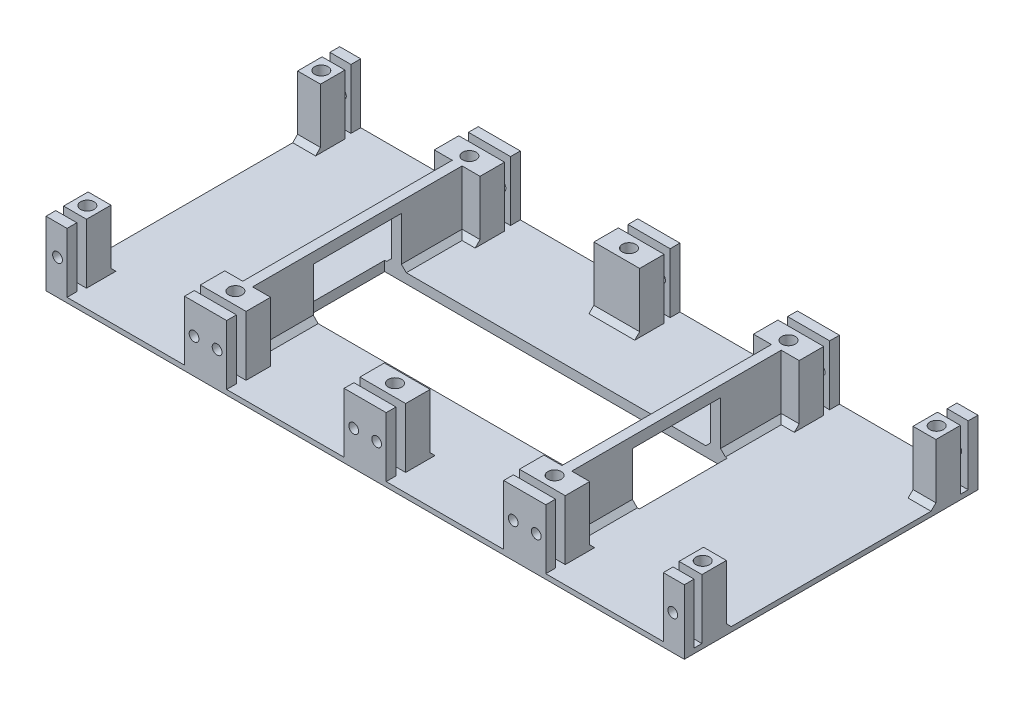
SolidWorks part; units mm, degrees
ref_plane "Alzado" through (0, 0, 0) normal (0, 0, 1) x (1, 0, 0)
ref_plane "Planta" through (0, 0, 0) normal (0, 1, 0) x (1, 0, 0)
ref_plane "Vista lateral" through (0, 0, 0) normal (1, 0, 0) x (0, 0, -1)
sketch "Croquis1" plane through (0, 0, 0) normal (0, 1, 0) x (1, 0, 0)
  line L1 (-65.2, 30) -> (65.2, 30)
  line L2 (-65.2, 30) -> (-65.2, -30)
  line L3 (-65.2, -30) -> (65.2, -30)
  line L4 (65.2, 30) -> (65.2, -30)
  line L5 (-65.2, 30) -> (65.2, -30) construction
  line L6 (-65.2, -30) -> (65.2, 30) construction
  point P0 (0, 0)
  dimension "D1" = 60
  dimension "D2" = 130.4
extrude "Saliente-Extruir1" add sketch "Croquis1" along normal blind 2
sketch "Croquis3" plane through (0, 0, 30) normal (0, 0, 1) x (1, 0, 0)
  line L0 (0, 0) -> (0, 26.1175) construction
  line L1 (-66, 8.1) -> (49934, 8.1) construction
  line L2 (-65.2, 2) -> (0, 2)
  line L3 (-65.2, 2) -> (-65.2, 14.2)
  line L4 (-65.2, 14.2) -> (0, 14.2)
  line L5 (0, 2) -> (0, 14.2)
  line L6 (-32.6, 14.2) -> (-32.6, 50014.2) construction
  line L7 (-65.2, 2) -> (65.2, 2) construction
  circle A0 centre (-62.85, 8.1) radius 1
  circle A1 centre (-34.95, 8.1) radius 1
  circle A4 centre (-30.25, 8.1) radius 1
  circle A5 centre (-2.35, 8.1) radius 1
  point P10 (-65.2, 8.1)
  point P11 (0, 8.1)
  point P22 (-32.6, 14.2)
  dimension "D2" = 2
  dimension "D1" = 12.2
  dimension "D3" = 2.35
  dimension "D4" = 2.35
extrude "Saliente-Extruir2" add sketch "Croquis3" against normal blind 2
sketch "Croquis5" plane through (0, 0, 30) normal (0, 0, 1) x (1, 0, 0)
  line L0 (-32.6, 14.2) -> (-32.6, 50014.2) construction
  line L1 (0, 14.2) -> (-65.2, 14.2) construction
  line L2 (-65.2, 2) -> (49934.8, 2) construction
  line L11 (-4.3, 2) -> (-28.3, 14.2) construction
  line L12 (-65.2, 14.2) -> (-32.6, 2) construction
  line L13 (-32.6, 2) -> (-32.6, 14.2) construction
  line L14 (0, 14.2) -> (-65.2, 14.2) construction
  line L15 (-32.6, 14.2) -> (-65.2, 2) construction
  line L16 (-48.9, 8.1) -> (-48.9, 50008.1) construction
  line L17 (-4.3, 14.2) -> (-28.3, 2) construction
  line L18 (-60.9, 14.2) -> (-36.9, 14.2)
  line L19 (-60.9, 14.2) -> (-60.9, 2)
  line L20 (-60.9, 2) -> (-36.9, 2)
  line L21 (-36.9, 14.2) -> (-36.9, 2)
  line L22 (-60.9, 14.2) -> (-36.9, 2) construction
  line L23 (-60.9, 2) -> (-36.9, 14.2) construction
  line L24 (-28.3, 14.2) -> (-28.3, 2)
  line L25 (-4.3, 2) -> (-28.3, 2)
  line L26 (-4.3, 14.2) -> (-4.3, 2)
  line L27 (-4.3, 14.2) -> (-28.3, 14.2)
  point P4 (-32.6, 14.2)
  point P19 (-48.9, 8.1)
  point P20 (-48.9, 8.1)
  point P31 (-16.3, 8.1)
  dimension "D1" = 24
extrude "Cortar-Extruir2" cut sketch "Croquis5" against normal up to next
sketch "Croquis6" plane through (0, 2, 0) normal (0, 1, 0) x (1, 0, 0)
  line L0 (-61.275, -26.4) -> (-50061.275, -26.4) construction
  line L1 (-60.525, -26.4) -> (-60.525, 49973.6) construction
  line L2 (-37.275, -26.4) -> (-37.275, 49973.6) construction
  line L3 (-27.925, -26.4) -> (-27.925, 49973.6) construction
  line L4 (-4.675, -26.4) -> (-4.675, 49973.6) construction
  line L5 (0, -1030) -> (0, -25.275) construction
  line L6 (-60.525, -21.4) -> (-50060.525, -21.4) construction
  line L7 (-65.2, 30) -> (-65.2, -28) construction
  line L8 (-65.2, -21.4) -> (-60.525, -21.4)
  line L9 (-65.2, -21.4) -> (-65.2, -26.4)
  line L10 (-65.2, -26.4) -> (-60.525, -26.4)
  line L11 (-60.525, -21.4) -> (-60.525, -26.4)
  line L12 (-65.2, -23.9) -> (49934.8, -23.9) construction
  line L13 (-37.275, -21.4) -> (-27.925, -21.4)
  line L14 (-37.275, -21.4) -> (-37.275, -26.4)
  line L15 (-37.275, -26.4) -> (-27.925, -26.4)
  line L16 (-27.925, -21.4) -> (-27.925, -26.4)
  line L17 (-4.675, -21.4) -> (0, -21.4)
  line L18 (-4.675, -21.4) -> (-4.675, -26.4)
  line L19 (-4.675, -26.4) -> (0, -26.4)
  line L20 (0, -21.4) -> (0, -22.525)
  line L21 (-62.8625, -21.4) -> (-62.8625, 49978.6) construction
  line L22 (-32.6, -21.4) -> (-32.6, 49978.6) construction
  line L23 (0, -22.525) -> (0, 49970) construction
  line L24 (0, -25.275) -> (0, -26.4)
  circle A0 centre (-62.8564, -23.9) radius 1.375
  circle A1 centre (-32.6, -23.9) radius 1.375
  arc A2 (0, -22.525) -> (0, -25.275) centre (0, -23.9) ccw
  point P37 (-65.2, -23.9)
  point P40 (-62.8625, -21.4)
  point P43 (-32.6, -21.4)
  dimension "D2" = 2.75
  dimension "D1" = 5
extrude "Saliente-Extruir3" add sketch "Croquis6" along normal up to vertex (12.2 mm away)
mirror "Simetría1" about plane through (0, 0, 0) normal (1, 0, 0) of "Saliente-Extruir3", "Saliente-Extruir2", "Cortar-Extruir2"
mirror "Simetría2" about plane through (0, 0, 0) normal (0, 0, 1) of "Simetría1", "Saliente-Extruir2", "Cortar-Extruir2", "Saliente-Extruir3"
chamfer "Chaflán1" distance 1 angle 45 4 edges at (65.2, 0, 0) (0, 0, -30) (0, 0, 30) (-65.2, 0, 0)
sketch "Croquis7" plane through (0, 2, 0) normal (0, 1, 0) x (1, 0, 0)
  line L0 (-32.6, 23.9) -> (-32.6, -49976.1) construction
  line L1 (32.6, 23.9) -> (32.6, -49976.1) construction
  line L2 (-27.925, 21.4) -> (-37.275, 21.4) construction
  line L3 (-33.6, -21.4) -> (-31.6, -21.4)
  line L4 (-33.6, -21.4) -> (-33.6, 21.4)
  line L5 (-33.6, 21.4) -> (-31.6, 21.4)
  line L6 (-31.6, -21.4) -> (-31.6, 21.4)
  line L7 (-33.6, -21.4) -> (-31.6, 21.4) construction
  line L8 (-33.6, 21.4) -> (-31.6, -21.4) construction
  line L9 (-27.925, -21.4) -> (-37.275, -21.4) construction
  line L10 (27.925, 21.4) -> (37.275, 21.4) construction
  line L11 (31.6, -21.4) -> (33.6, -21.4)
  line L12 (31.6, -21.4) -> (31.6, 21.4)
  line L13 (31.6, 21.4) -> (33.6, 21.4)
  line L14 (33.6, -21.4) -> (33.6, 21.4)
  line L15 (31.6, -21.4) -> (33.6, 21.4) construction
  line L16 (31.6, 21.4) -> (33.6, -21.4) construction
  line L17 (27.925, -21.4) -> (37.275, -21.4) construction
  point P6 (-32.6, 0)
  point P16 (32.6, 0)
  dimension "D1" = 2
  dimension "D2" = 2
extrude "Saliente-Extruir4" add sketch "Croquis7" along normal up to surface (12.2 mm away) up to face at (-32.6, 14.2, -25.275)
chamfer "Chaflán2" distance 1 angle 45 11 edges at (62.8625, 2, -21.4) (29.7625, 2, -21.4) (0, 2, -21.4) (-62.8625, 2, -21.4) (-29.7625, 2, -21.4) (-35.4375, 2, -21.4) (-31.6, 2, 0) (-33.6, 2, 0) (35.4375, 2, -21.4) (33.6, 2, 0) (31.6, 2, 0)
sketch "Croquis9" plane through (0, 0, 0) normal (0, -1, 0) x (1, 0, 0)
  line L1 (35, -9) -> (-35, -9)
  line L2 (35, -9) -> (35, 9)
  line L3 (35, 9) -> (-35, 9)
  line L4 (-35, -9) -> (-35, 9)
  line L5 (35, -9) -> (-35, 9) construction
  line L6 (35, 9) -> (-35, -9) construction
  point P4 (0, 0)
  point P5 (0, 0)
  point P7 (0, 0)
  point P11 (0, 0)
  dimension "D1" = 18
  dimension "D2" = 70
extrude "Cortar-Extruir4" cut sketch "Croquis9" against normal blind 12
